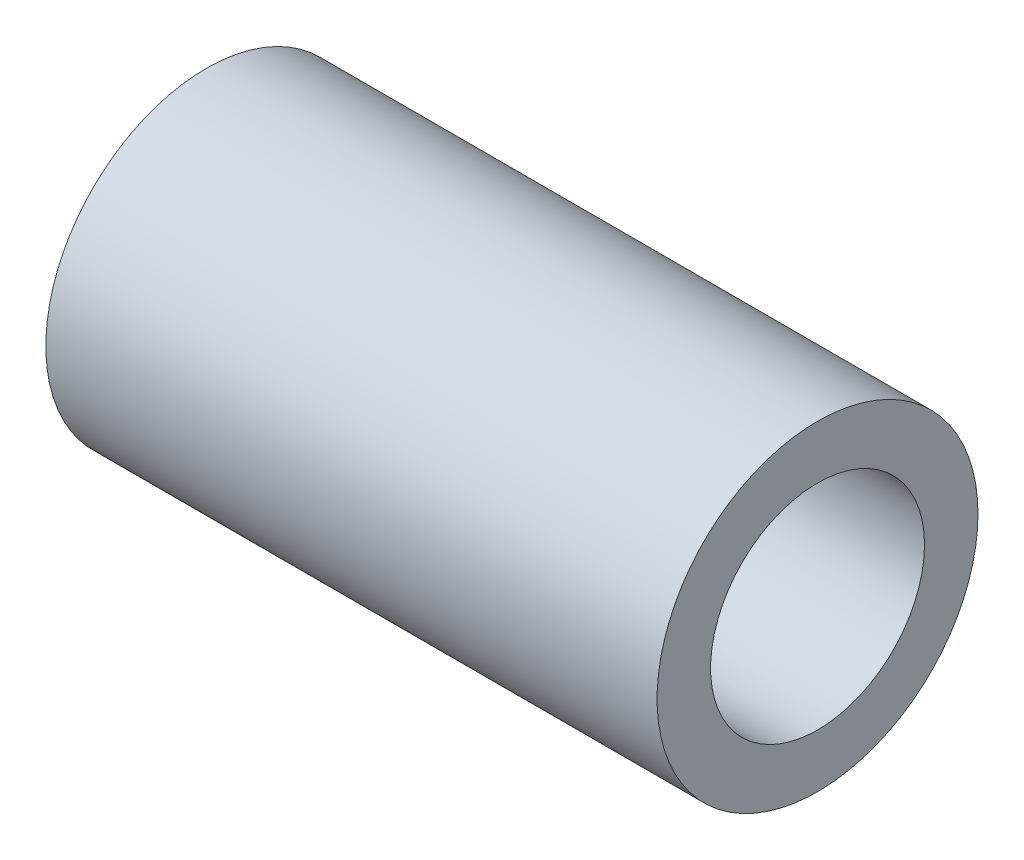
SolidWorks part; units mm, degrees
ref_plane "Front Plane" through (0, 0, 0) normal (0, 0, 1) x (1, 0, 0)
ref_plane "Top Plane" through (0, 0, 0) normal (0, 1, 0) x (1, 0, 0)
ref_plane "Right Plane" through (0, 0, 0) normal (1, 0, 0) x (0, 0, -1)
sketch "Sketch1" plane through (0, 0, 0) normal (1, 0, 0) x (0, 0, -1)
  circle A0 centre (0, 0) radius 1.575
  circle A1 centre (0, 0) radius 1.05
  dimension "D1" = 3.15
  dimension "D2" = 2.1
extrude "Boss-Extrude1" add sketch "Sketch1" along normal blind 6
